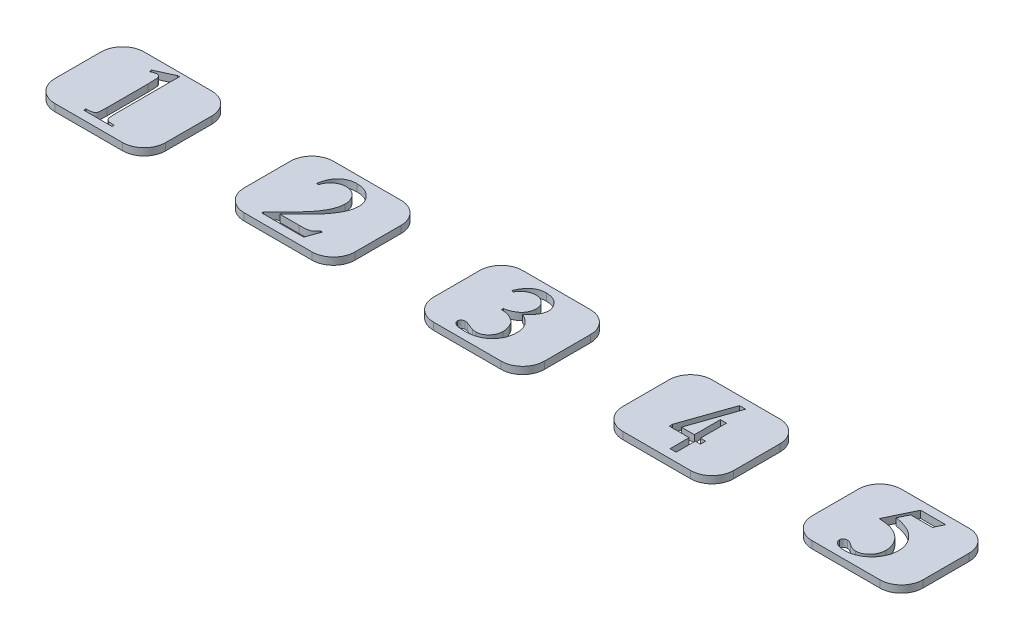
SolidWorks part; units mm, degrees
ref_plane "Front Plane" through (0, 0, 0) normal (0, 0, 1) x (1, 0, 0)
ref_plane "Top Plane" through (0, 0, 0) normal (0, 1, 0) x (1, 0, 0)
ref_plane "Right Plane" through (0, 0, 0) normal (1, 0, 0) x (0, 0, -1)
sketch "Sketch1" plane through (0, 0, 0) normal (0, 1, 0) x (1, 0, 0)
  line L5 (-74.9608, -8.0786) -> (-65.5608, -8.0786)
  line L7 (-77.9608, -5.0786) -> (-77.9608, 1.3214)
  line L8 (-74.9608, 4.3214) -> (-65.5608, 4.3214)
  line L9 (-62.5608, -5.0786) -> (-62.5608, 1.3214)
  line L10 (-77.9608, -8.0786) -> (-62.5608, 4.3214) construction
  line L11 (-77.9608, 4.3214) -> (-62.5608, -8.0786) construction
  line L27 (-75.2608, -6.8786) -> (-65.2608, -6.8786) construction
  line L28 (-51.6608, -5.0786) -> (-51.6608, 1.3214)
  line L33 (-48.6608, -8.0786) -> (-39.2608, -8.0786)
  line L36 (-36.2608, -5.0786) -> (-36.2608, 1.3214)
  line L41 (-48.6608, 4.3214) -> (-39.2608, 4.3214)
  line L44 (-51.6608, 4.3214) -> (-36.2608, -8.0786) construction
  line L49 (-51.6608, -8.0786) -> (-36.2608, 4.3214) construction
  line L50 (-25.3608, -5.0786) -> (-25.3608, 1.3214)
  line L51 (-22.3608, -8.0786) -> (-12.9608, -8.0786)
  line L52 (-9.9608, -5.0786) -> (-9.9608, 1.3214)
  line L57 (-22.3608, 4.3214) -> (-12.9608, 4.3214)
  line L58 (-25.3608, 4.3214) -> (-9.9608, -8.0786) construction
  line L59 (-25.3608, -8.0786) -> (-9.9608, 4.3214) construction
  line L60 (-22.6608, -6.8786) -> (-12.6608, -6.8786) construction
  line L61 (3.6392, -6.8786) -> (13.6392, -6.8786) construction
  line L64 (0.9392, -5.0786) -> (0.9392, 1.3214)
  line L65 (3.9392, -8.0786) -> (13.3392, -8.0786)
  line L66 (16.3392, -5.0786) -> (16.3392, 1.3214)
  line L67 (3.9392, 4.3214) -> (13.3392, 4.3214)
  line L68 (0.9392, 4.3214) -> (16.3392, -8.0786) construction
  line L69 (0.9392, -8.0786) -> (16.3392, 4.3214) construction
  line L70 (27.2392, -5.0786) -> (27.2392, 1.3214)
  line L71 (30.2392, -8.0786) -> (39.6392, -8.0786)
  line L72 (42.6392, -5.0786) -> (42.6392, 1.3214)
  line L73 (30.2392, 4.3214) -> (39.6392, 4.3214)
  line L74 (27.2392, 4.3214) -> (42.6392, -8.0786) construction
  line L75 (27.2392, -8.0786) -> (42.6392, 4.3214) construction
  line L76 (-77.9608, -5.0786) -> (-51.6608, -5.0786) construction
  line L77 (-48.9608, -6.8786) -> (-38.9608, -6.8786) construction
  arc A0 (-74.9608, -8.0786) -> (-77.9608, -5.0786) centre (-74.9608, -5.0786) cw
  arc A1 (-65.5608, -8.0786) -> (-62.5608, -5.0786) centre (-65.5608, -5.0786) ccw
  arc A2 (-65.5608, 4.3214) -> (-62.5608, 1.3214) centre (-65.5608, 1.3214) cw
  arc A3 (-74.9608, 4.3214) -> (-77.9608, 1.3214) centre (-74.9608, 1.3214) ccw
  arc A40 (-48.6608, 4.3214) -> (-51.6608, 1.3214) centre (-48.6608, 1.3214) ccw
  arc A41 (-48.6608, -8.0786) -> (-51.6608, -5.0786) centre (-48.6608, -5.0786) cw
  arc A42 (-39.2608, -8.0786) -> (-36.2608, -5.0786) centre (-39.2608, -5.0786) ccw
  arc A43 (-39.2608, 4.3214) -> (-36.2608, 1.3214) centre (-39.2608, 1.3214) cw
  arc A44 (-22.3608, 4.3214) -> (-25.3608, 1.3214) centre (-22.3608, 1.3214) ccw
  arc A45 (-22.3608, -8.0786) -> (-25.3608, -5.0786) centre (-22.3608, -5.0786) cw
  arc A46 (-12.9608, -8.0786) -> (-9.9608, -5.0786) centre (-12.9608, -5.0786) ccw
  arc A47 (-12.9608, 4.3214) -> (-9.9608, 1.3214) centre (-12.9608, 1.3214) cw
  arc A48 (3.9392, 4.3214) -> (0.9392, 1.3214) centre (3.9392, 1.3214) ccw
  arc A49 (3.9392, -8.0786) -> (0.9392, -5.0786) centre (3.9392, -5.0786) cw
  arc A50 (13.3392, -8.0786) -> (16.3392, -5.0786) centre (13.3392, -5.0786) ccw
  arc A51 (13.3392, 4.3214) -> (16.3392, 1.3214) centre (13.3392, 1.3214) cw
  arc A52 (30.2392, 4.3214) -> (27.2392, 1.3214) centre (30.2392, 1.3214) ccw
  arc A53 (30.2392, -8.0786) -> (27.2392, -5.0786) centre (30.2392, -5.0786) cw
  arc A54 (39.6392, -8.0786) -> (42.6392, -5.0786) centre (39.6392, -5.0786) ccw
  arc A55 (39.6392, 4.3214) -> (42.6392, 1.3214) centre (39.6392, 1.3214) cw
  text T0 "1" font "Times New Roman" height in points 41
  text T1 "2" font "Times New Roman" height 10
  text T2 "3" font "Times New Roman" height 10
  text T3 "4" font "Agency FB" height 10
  text T4 "5" font "Times New Roman" height 10
  point P0 (-70.2608, -1.8786)
  point P59 (-17.6608, -1.8786)
  point P94 (-43.9608, -1.8786)
  point P96 (8.6392, -1.8786)
  dimension "D3" = 3
  dimension "D1" = 15.4
  dimension "D2" = 5
  dimension "D5" = 5
  dimension "D6" = 10
  dimension "D7" = 5
  dimension "D4" = 26.3
  dimension "D8" = 5
  dimension "D9" = 10
  dimension "D10" = 5
  dimension "D11" = 5
  dimension "D12" = 10
  dimension "D13" = 5
  dimension "D14" = 10
  dimension "D15" = 5
  dimension "D16" = 5
extrude "Boss-Extrude2" add sketch "Sketch1" along normal blind 1
